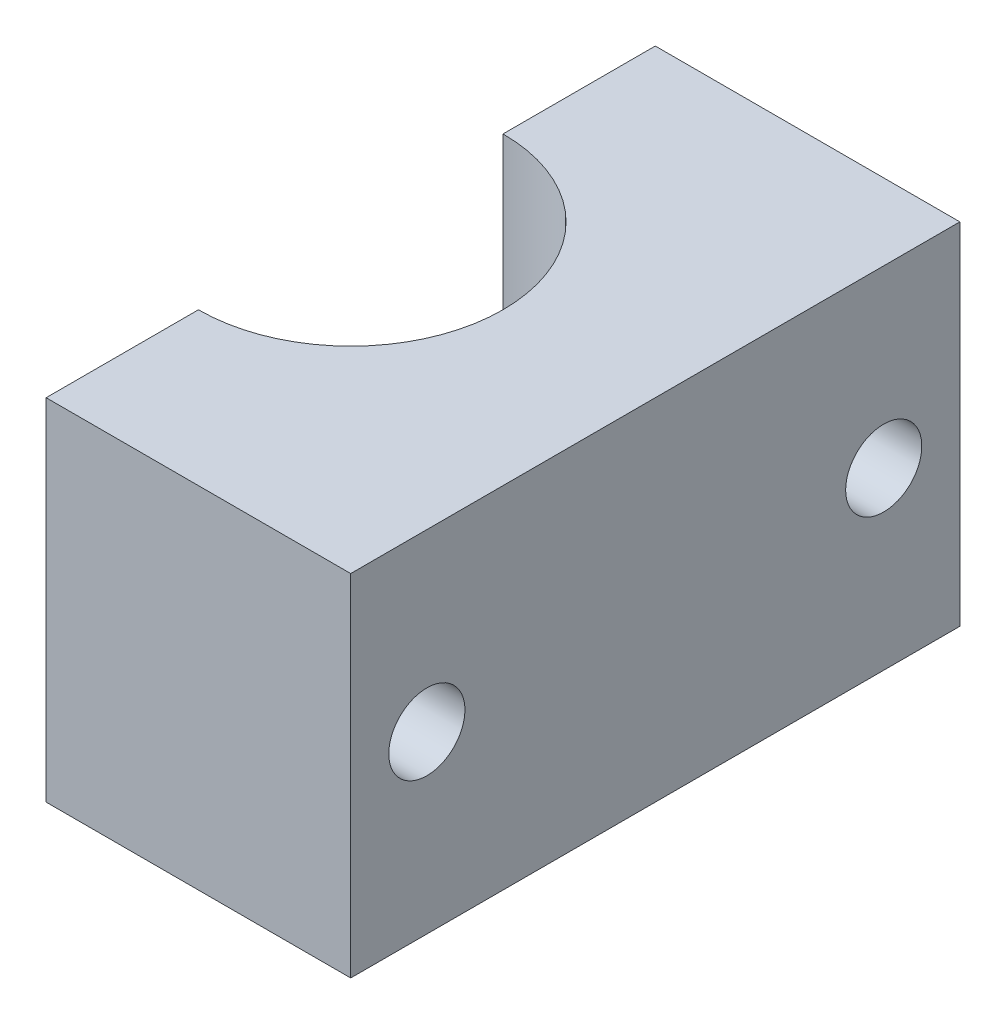
SolidWorks part; units mm, degrees
ref_plane "Front Plane" through (0, 0, 0) normal (0, 0, 1) x (1, 0, 0)
ref_plane "Top Plane" through (0, 0, 0) normal (0, 1, 0) x (1, 0, 0)
ref_plane "Right Plane" through (0, 0, 0) normal (1, 0, 0) x (0, 0, -1)
sketch "Sketch1" plane through (0, 0, 0) normal (0, 1, 0) x (1, 0, 0)
  line L1 (0, 0) -> (25.4, 0)
  line L2 (0, 0) -> (0, 50.8)
  line L3 (0, 50.8) -> (25.4, 50.8)
  line L4 (25.4, 0) -> (25.4, 50.8)
  dimension "D1" = 25.4
  dimension "D2" = 50.8
extrude "Boss-Extrude1" add sketch "Sketch1" along normal blind 29.21
sketch "Sketch2" plane through (0, 29.21, 0) normal (0, 1, 0) x (1, 0, 0)
  line L0 (0, 50.8) -> (0, 0) construction
  circle A0 centre (0, 25.4) radius 12.7
  dimension "D1" = 25.4
extrude "Cut-Extrude1" cut sketch "Sketch2" against normal through all
sketch "Sketch4" plane through (0, 0, 0) normal (-1, 0, 0) x (0, 0, 1)
  line L0 (-50.8, 29.21) -> (-50.8, 0) construction
  line L1 (-50.8, 29.21) -> (-38.1, 29.21) construction
  circle A0 centre (-44.45, 14.605) radius 3.175
  dimension "D1" = 6.35
  dimension "D2" = 6.35
  dimension "D3" = 14.605
extrude "Cut-Extrude2" cut sketch "Sketch4" against normal through all
sketch "Sketch5" plane through (0, 0, 0) normal (-1, 0, 0) x (0, 0, 1)
  line L0 (0, 29.21) -> (0, 0) construction
  line L1 (-12.7, 29.21) -> (0, 29.21) construction
  circle A0 centre (-6.35, 14.605) radius 3.175
  dimension "D1" = 6.35
  dimension "D2" = 6.35
  dimension "D3" = 14.605
extrude "Cut-Extrude3" cut sketch "Sketch5" against normal through all
